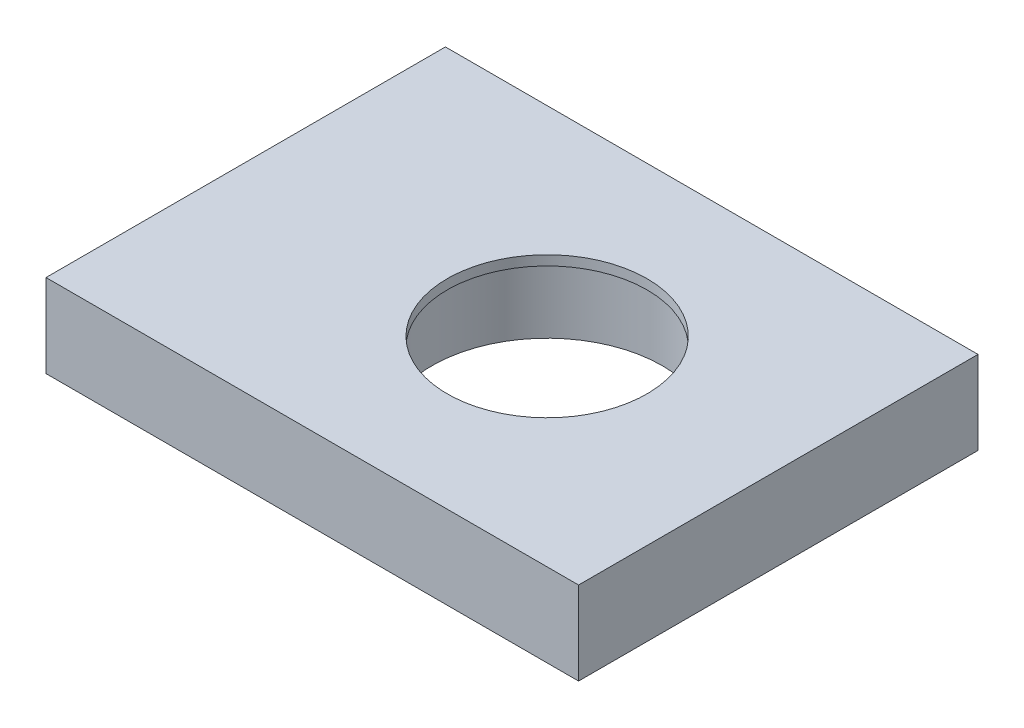
SolidWorks part; units mm, degrees
ref_plane "Front Plane" through (0, 0, 0) normal (0, 0, 1) x (1, 0, 0)
ref_plane "Top Plane" through (0, 0, 0) normal (0, 1, 0) x (1, 0, 0)
ref_plane "Right Plane" through (0, 0, 0) normal (1, 0, 0) x (0, 0, -1)
sketch "Sketch1" plane through (0, 0, 0) normal (0, 1, 0) x (1, 0, 0)
  line L1 (-25.4, -19.05) -> (25.4, -19.05)
  line L2 (-25.4, -19.05) -> (-25.4, 19.05)
  line L3 (-25.4, 19.05) -> (25.4, 19.05)
  line L4 (25.4, -19.05) -> (25.4, 19.05)
  line L5 (-25.4, -19.05) -> (25.4, 19.05) construction
  line L6 (-25.4, 19.05) -> (25.4, -19.05) construction
  point P0 (0, 0)
  dimension "D1" = 38.1
  dimension "D2" = 50.8
extrude "Body" add sketch "Sketch1" along normal blind 7.9375
sketch "Sketch 1" plane through (0, 0, 0) normal (0, -1, 0) x (1, 0, 0)
  line L0 (0, 0) -> (3.3528, 0) construction
  line L2 (-25.4, -19.05) -> (-25.4, 19.05) construction
  circle A0 centre (3.3528, 0) radius 9.525
  dimension "D1" = 19.05
  dimension "D2" = 28.7528
extrude "Thru Hole" cut sketch "Sketch 1" against normal through all
sketch "Sketch4" plane through (0, 0, 0) normal (0, -1, 0) x (1, 0, 0)
  circle A0 centre (3.3528, 0) radius 10.9982
  dimension "D1" = 21.9964
extrude "Bearing Bore" cut sketch "Sketch4" against normal blind 7.0104
sketch "Sketch5" plane through (0, 0, 0) normal (0, -1, 0) x (1, 0, 0)
  line L0 (-21.4249, 14.986) -> (-21.4249, -14.986) construction
  line L1 (-25.4, 0) -> (-17.4498, 0) construction
  line L2 (-25.4, 19.05) -> (-25.4, -19.05) construction
  line L3 (-25.4, -19.05) -> (-17.4498, -19.05) construction
  line L4 (-17.4498, -19.05) -> (-17.4498, 19.05) construction
  line L5 (-17.4498, 19.05) -> (-25.4, 19.05) construction
  line L8 (-25.4, -19.05) -> (-25.4, 19.05) construction
  line L9 (-25.4, 19.05) -> (25.4, 19.05) construction
  line L10 (25.4, -19.05) -> (-25.4, -19.05) construction
  circle A0 centre (-21.4249, 14.986) radius 1.4986
  circle A1 centre (-21.4249, 4.9953) radius 1.4986
  circle A2 centre (-21.4249, -14.986) radius 1.4986
  circle A3 centre (-21.4249, -4.9953) radius 1.4986
  point P16 (-35.4092, 14.6328)
  point P23 (-25.4, 0)
  point P24 (-19.6727, 0)
  point P25 (0, 0)
  point P26 (-21.4249, 0)
  point P27 (-21.4249, 0)
  point P28 (0, 0)
  point P29 (0, 0)
  point P30 (-22.225, 15.7614)
  dimension "D3" = 2.9972
  dimension "D4" = 2.9972
  dimension "D5" = 2.9972
  dimension "D6" = 2.9972
  dimension "D1" = 7.9502
  dimension "D2" = 29.972
  dimension "D7" = 9.9907
  dimension "D8" = 19.9813
extrude "Dowel Holes" cut sketch "Sketch5" against normal blind 6.5
equation "\"D4@Sketch5\"=\"D3@Sketch5\""
equation "\"D5@Sketch5\"=\"D3@Sketch5\""
equation "\"D6@Sketch5\"=\"D3@Sketch5\""
equation "\"D7@Sketch5\"=\"D2@Sketch5\"/3"
equation "\"D8@Sketch5\"=2*\"D2@Sketch5\"/3"
